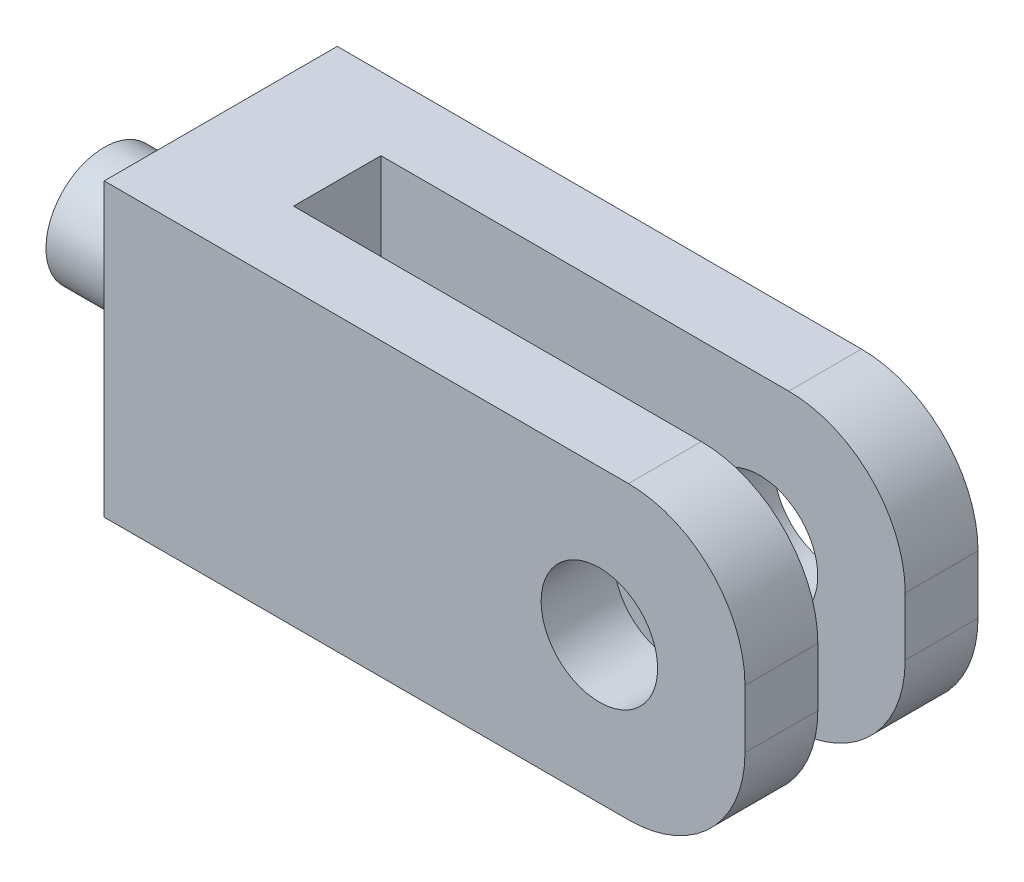
SolidWorks part; units mm, degrees
ref_plane "Front Plane" through (0, 0, 0) normal (0, 0, 1) x (1, 0, 0)
ref_plane "Top Plane" through (0, 0, 0) normal (0, 1, 0) x (1, 0, 0)
ref_plane "Right Plane" through (0, 0, 0) normal (1, 0, 0) x (0, 0, -1)
sketch "Sketch1" plane through (0, 0, 0) normal (0, 0, 1) x (1, 0, 0)
  line L1 (-55, 25) -> (55, 25)
  line L2 (-55, 25) -> (-55, -25)
  line L3 (-55, -25) -> (55, -25)
  line L4 (55, 25) -> (55, -25)
  line L5 (-55, 25) -> (55, -25) construction
  line L6 (-55, -25) -> (55, 25) construction
  point P0 (0, 0)
  dimension "D1" = 110
  dimension "D2" = 50
extrude "Boss-Extrude1" add sketch "Sketch1" along normal blind 40
sketch "Sketch2" plane through (55, 0, 0) normal (1, 0, 0) x (0, 0, -1)
  line L0 (-40, -25) -> (0, -25) construction
  line L1 (-27.5, 25) -> (-12.5, 25)
  line L2 (-27.5, 25) -> (-27.5, -25)
  line L3 (-27.5, -25) -> (-12.5, -25)
  line L4 (-12.5, 25) -> (-12.5, -25)
  line L5 (-27.5, 25) -> (-12.5, -25) construction
  line L6 (-27.5, -25) -> (-12.5, 25) construction
  line L7 (0, -25) -> (0, 25) construction
  point P0 (-20, 0)
  dimension "D1" = 15
  dimension "D2" = 20
  dimension "D3" = 15
extrude "Cut-Extrude1" cut sketch "Sketch2" against normal blind 90
fillet "Fillet1" radius 20 4 edges at (55, -25, 33.75) (55, -25, 6.25) (55, 25, 6.25) (55, 25, 33.75)
sketch "Sketch3" plane through (0, 0, 0) normal (0, 0, -1) x (-1, 0, 0)
  line L0 (55, -25) -> (-35, -25) construction
  circle A0 centre (-30, 0) radius 10
  dimension "D1" = 20
  dimension "D2" = 25
  dimension "D3" = 25
  dimension "D4" = 30
extrude "Cut-Extrude2" cut sketch "Sketch3" against normal blind 90
sketch "Sketch4" plane through (-55, 0, 0) normal (-1, 0, 0) x (0, 0, 1)
  line L0 (40, 25) -> (0, -25) construction
  circle A0 centre (20, 0) radius 10
  dimension "D1" = 20
extrude "Boss-Extrude2" add sketch "Sketch4" along normal blind 20
